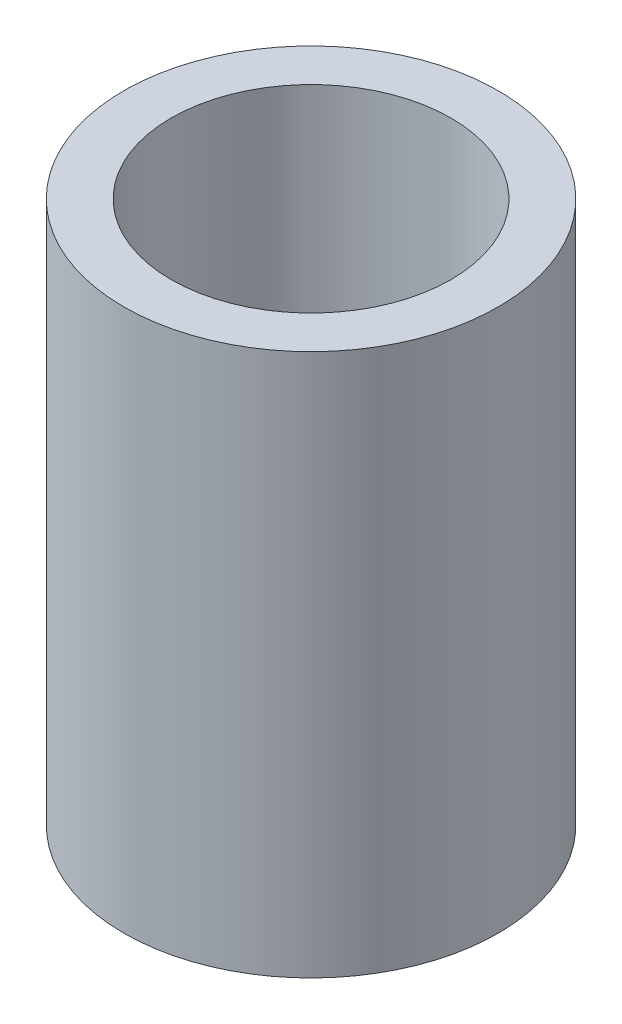
SolidWorks part; units mm, degrees
material "Nickel"
ref_plane "Front Plane" through (0, 0, 0) normal (0, 0, 1) x (1, 0, 0)
ref_plane "Top Plane" through (0, 0, 0) normal (0, 1, 0) x (1, 0, 0)
ref_plane "Right Plane" through (0, 0, 0) normal (1, 0, 0) x (0, 0, -1)
sketch "Sketch1" plane through (0, 0, 0) normal (0, 1, 0) x (1, 0, 0)
  circle A0 centre (0, 0) radius 4.3663
  circle A1 centre (0, 0) radius 3.2639
  dimension "D1" = 8.7325
  dimension "D2" = 6.5278
extrude "Boss-Extrude1" add sketch "Sketch1" along normal blind 12.6492
